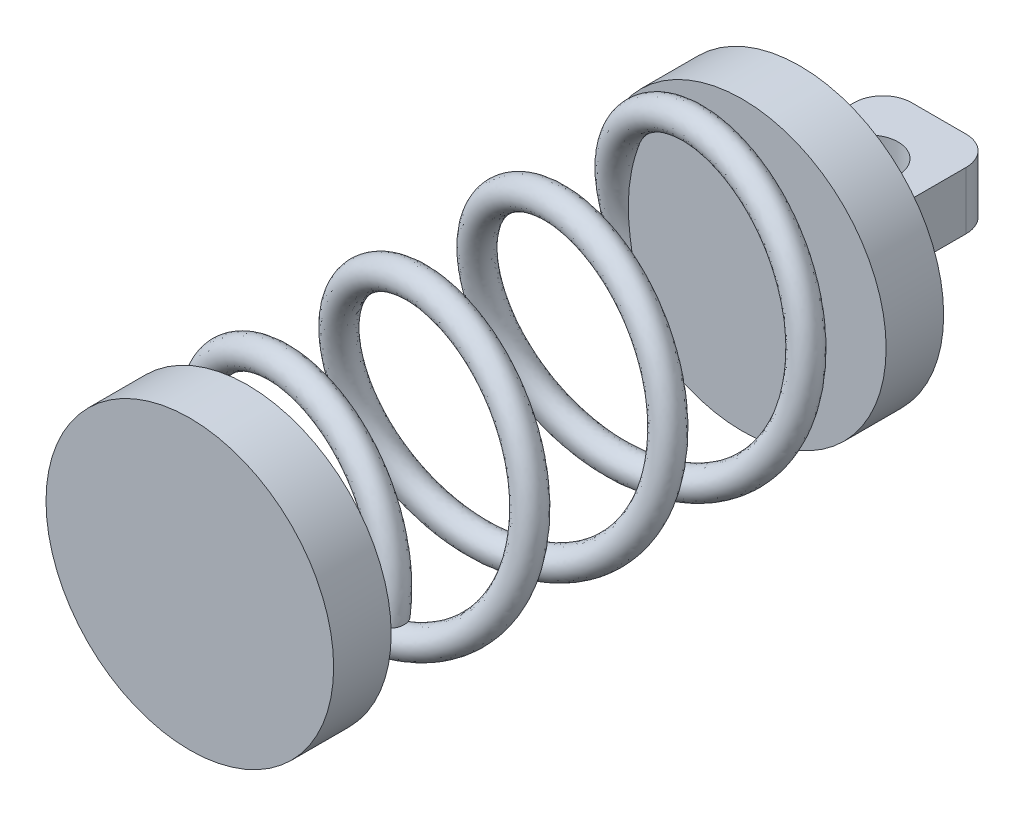
SolidWorks part; units mm, degrees
ref_plane "Front Plane" through (0, 0, 0) normal (0, 0, 1) x (1, 0, 0)
ref_plane "Top Plane" through (0, 0, 0) normal (0, 1, 0) x (1, 0, 0)
ref_plane "Right Plane" through (0, 0, 0) normal (1, 0, 0) x (0, 0, -1)
sketch "Sketch1" plane through (0, 0, 0) normal (0, 0, 1) x (1, 0, 0)
  circle A0 centre (0, 0) radius 25
  dimension "D1" = 50
extrude "Boss-Extrude1" add sketch "Sketch1" along normal blind 10
sketch "Sketch2" plane through (0, 0, 0) normal (0, 1, 0) x (1, 0, 0)
  line L0 (25, 0) -> (-25, 0) construction
  circle A0 centre (-22.25, 2.5) radius 2.5
  dimension "D1" = 5
  dimension "D3" = 22.25
  dimension "D2" = 2.5
sketch "Sketch3" plane through (0, 0, 0) normal (0, 1, 0) x (1, 0, 0)
  circle A0 centre (-22.25, 2.5) radius 2.5
ref_plane "Plane1" through (0, 0, -2.5) normal (0, 0, -1) x (-1, 0, 0)
sketch "Sketch5" plane through (0, 0, -2.5) normal (0, 0, -1) x (-1, 0, 0)
  circle A0 centre (0, 0) radius 22.25
  dimension "D1" = 44.5
curve "Helix/Spiral1" pitch 24 height 90 turns 3.75
sketch "Sketch6" plane through (0, 0, 0) normal (0, 1, 0) x (1, 0, 0)
  line L0 (27.5, 2.5) -> (-27.5, 2.5) construction
  circle A0 centre (22.25, 2.5) radius 2.5
  spline S0 degree 3 poles (22.25, 2.5) (22.25, 2.8832) (21.5681, 3.6545) (18.592, 4.8075) (13.9323, 5.9616) (8.0109, 7.1154) (1.364, 8.2692) (-5.4064, 9.4231) (-11.6872, 10.5769) (-16.9096, 11.7308) (-20.6007, 12.8846) (-22.4263, 14.0385) (-22.2209, 15.1923) (-20.0033, 16.3462) (-15.9742, 17.5) (-10.4985, 18.6538) (-4.0721, 19.8077) (2.723, 20.9615) (9.2716, 22.1154) (14.9806, 23.2692) (19.3329, 24.4231) (21.9345, 25.5769) (22.5498, 26.7308) (21.1229, 27.8846) (17.7832, 29.0385) (12.8331, 30.1923) (4.6835, 31.7308) (-4.6835, 33.2692) (-12.8331, 34.8077) (-17.7832, 35.9615) (-21.1229, 37.1154) (-22.5498, 38.2692) (-21.9345, 39.4231) (-19.3329, 40.5769) (-14.9806, 41.7308) (-9.2716, 42.8846) (-2.723, 44.0385) (4.0721, 45.1923) (10.4985, 46.3462) (15.9742, 47.5) (20.0033, 48.6538) (22.2209, 49.8077) (22.4263, 50.9615) (20.6007, 52.1154) (16.9096, 53.2692) (11.6872, 54.4231) (5.4064, 55.5769) (-1.364, 56.7308) (-8.0109, 57.8846) (-13.9323, 59.0385) (-18.592, 60.1923) (-21.5681, 61.3462) (-22.591, 62.5) (-21.5681, 63.6538) (-18.592, 64.8077) (-13.9323, 65.9615) (-8.0109, 67.1154) (-1.364, 68.2692) (5.4064, 69.4231) (11.6872, 70.5769) (16.9096, 71.7308) (20.6007, 72.8846) (22.4263, 74.0385) (22.2209, 75.1923) (20.0033, 76.3462) (15.9742, 77.5) (10.4985, 78.6538) (4.0721, 79.8077) (-2.723, 80.9615) (-9.2716, 82.1154) (-14.9806, 83.2692) (-19.3329, 84.4231) (-21.9345, 85.5769) (-22.5498, 86.7308) (-21.1228, 87.8846) (-17.7835, 89.0384) (-12.8321, 90.1925) (-6.7247, 91.3455) (-2.2321, 92.1168) (0, 92.5) knots 0 0 0 0 0.012821 0.025641 0.038462 0.051282 0.064103 0.076923 0.089744 0.102564 0.115385 0.128205 0.141026 0.153846 0.166667 0.179487 0.192308 0.205128 0.217949 0.230769 0.24359 0.25641 0.269231 0.282051 0.294872 0.307692 0.320513 0.346154 0.358974 0.371795 0.384615 0.397436 0.410256 0.423077 0.435897 0.448718 0.461538 0.474359 0.487179 0.5 0.512821 0.525641 0.538462 0.551282 0.564103 0.576923 0.589744 0.602564 0.615385 0.628205 0.641026 0.653846 0.666667 0.679487 0.692308 0.705128 0.717949 0.730769 0.74359 0.75641 0.769231 0.782051 0.794872 0.807692 0.820513 0.833333 0.846154 0.858974 0.871795 0.884615 0.897436 0.910256 0.923077 0.935897 0.948718 0.961538 0.974359 0.987179 1 1 1 1 construction
  dimension "D1" = 5
sweep "Sweep1" add profiles "Sketch6" path "Helix/Spiral1"
sketch "Sketch7" plane through (0, 0, 0) normal (1, 0, 0) x (0, 0, -1)
  line L0 (2.5, 0) -> (91.0336, 0) construction
  line L1 (5, 0) -> (0, 0) construction
  line L2 (91.0336, -20.6306) -> (91.0336, 17.0398) construction
  spline S0 degree 3 poles (2.5, 0) (2.8832, 2.2321) (3.6545, 6.7247) (4.8075, 12.8321) (5.9616, 17.7835) (7.1154, 21.1228) (8.2692, 22.5498) (9.4231, 21.9345) (10.5769, 19.3329) (11.7308, 14.9806) (12.8846, 9.2716) (14.0385, 2.723) (15.1923, -4.0721) (16.3462, -10.4985) (17.5, -15.9742) (18.6538, -20.0033) (19.8077, -22.2209) (20.9615, -22.4263) (22.1154, -20.6007) (23.2692, -16.9096) (24.4231, -11.6872) (25.5769, -5.4064) (26.7308, 1.364) (27.8846, 8.0109) (29.0385, 13.9323) (30.1923, 18.592) (31.3462, 21.5681) (32.5, 22.591) (33.6538, 21.5681) (34.8077, 18.592) (35.9615, 13.9323) (37.1154, 8.0109) (38.2692, 1.364) (39.4231, -5.4064) (40.5769, -11.6872) (41.7308, -16.9096) (42.8846, -20.6007) (44.0385, -22.4263) (45.1923, -22.2209) (46.3462, -20.0033) (47.5, -15.9742) (48.6538, -10.4985) (49.8077, -4.0721) (50.9615, 2.723) (52.1154, 9.2716) (53.2692, 14.9806) (54.4231, 19.3329) (55.5769, 21.9345) (56.7308, 22.5498) (57.8846, 21.1229) (59.0385, 17.7832) (60.1923, 12.8331) (61.7308, 4.6835) (63.2692, -4.6835) (64.8077, -12.8331) (65.9615, -17.7832) (67.1154, -21.1229) (68.2692, -22.5498) (69.4231, -21.9345) (70.5769, -19.3329) (71.7308, -14.9806) (72.8846, -9.2716) (74.0385, -2.723) (75.1923, 4.0721) (76.3462, 10.4985) (77.5, 15.9742) (78.6538, 20.0033) (79.8077, 22.2209) (80.9615, 22.4263) (82.1154, 20.6007) (83.2692, 16.9096) (84.4231, 11.6872) (85.5769, 5.4064) (86.7308, -1.364) (87.8846, -8.0109) (89.0384, -13.9323) (90.1925, -18.592) (91.3455, -21.5681) (92.1168, -22.25) (92.5, -22.25) knots 0 0 0 0 0.012821 0.025641 0.038462 0.051282 0.064103 0.076923 0.089744 0.102564 0.115385 0.128205 0.141026 0.153846 0.166667 0.179487 0.192308 0.205128 0.217949 0.230769 0.24359 0.25641 0.269231 0.282051 0.294872 0.307692 0.320513 0.333333 0.346154 0.358974 0.371795 0.384615 0.397436 0.410256 0.423077 0.435897 0.448718 0.461538 0.474359 0.487179 0.5 0.512821 0.525641 0.538462 0.551282 0.564103 0.576923 0.589744 0.602564 0.615385 0.628205 0.641026 0.653846 0.679487 0.692308 0.705128 0.717949 0.730769 0.74359 0.75641 0.769231 0.782051 0.794872 0.807692 0.820513 0.833333 0.846154 0.858974 0.871795 0.884615 0.897436 0.910256 0.923077 0.935897 0.948718 0.961538 0.974359 0.987179 1 1 1 1 construction
ref_plane "Plane2" through (0, 0, -91.0336) normal (0, 0, -1) x (-1, 0, 0)
sketch "Sketch8" plane through (0, 0, -91.0336) normal (0, 0, -1) x (-1, 0, 0)
  circle A0 centre (0, 0) radius 25
extrude "Boss-Extrude2" add sketch "Sketch8" along normal mid plane 10
sketch "Sketch9" plane through (0, 0, 0) normal (0, 1, 0) x (1, 0, 0)
  line L0 (25, 96.0336) -> (-25, 96.0336) construction
  line L1 (4.7374, 120.2051) -> (-4.7374, 120.2051)
  line L2 (9.7374, 115.2051) -> (9.7374, 96.0336)
  line L3 (9.7374, 96.0336) -> (-9.7374, 96.0336)
  line L4 (-9.7374, 115.2051) -> (-9.7374, 96.0336)
  line L5 (9.7374, 120.2051) -> (-9.7374, 96.0336) construction
  line L6 (9.7374, 96.0336) -> (-9.7374, 120.2051) construction
  arc A0 (4.7374, 120.2051) -> (9.7374, 115.2051) centre (4.7374, 115.2051) cw
  arc A1 (-4.7374, 120.2051) -> (-9.7374, 115.2051) centre (-4.7374, 115.2051) ccw
  circle A2 centre (0, 108.1194) radius 5
  point P0 (0, 108.1194)
  dimension "D1" = 5
  dimension "D2" = 10
extrude "Boss-Extrude3" add sketch "Sketch9" along normal mid plane 10
